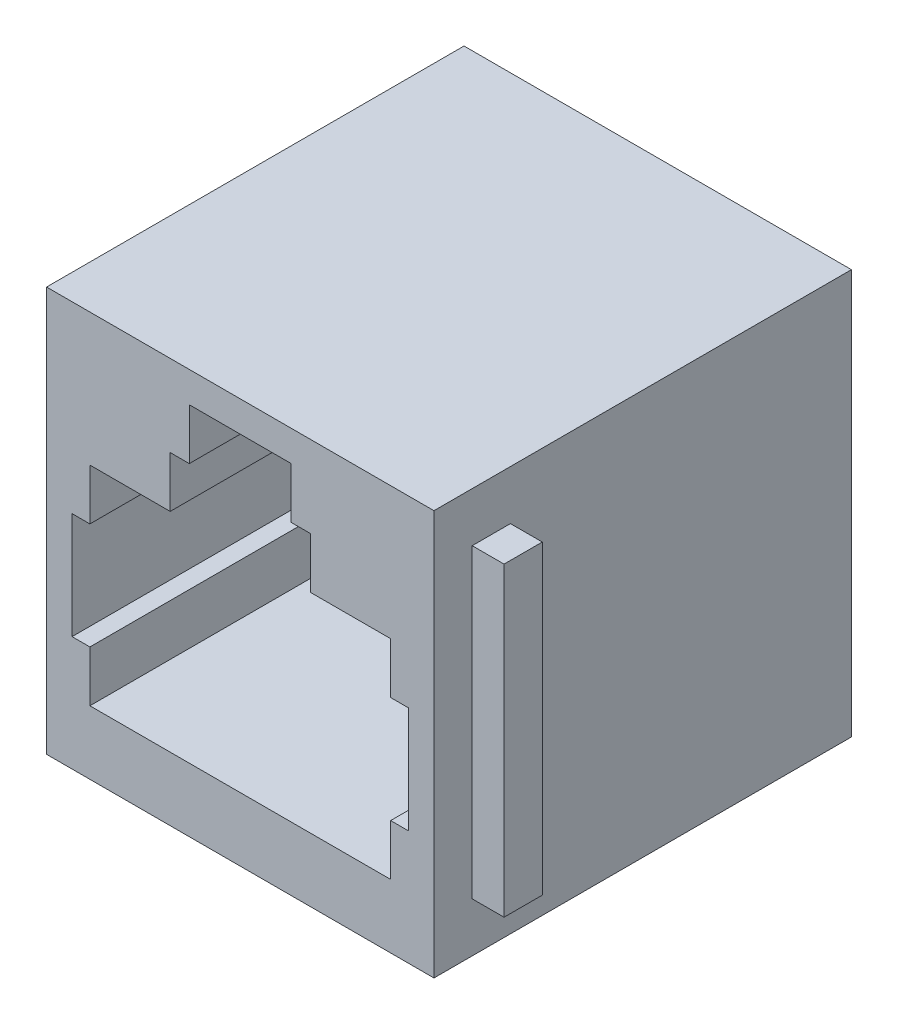
SolidWorks part; units mm, degrees
ref_plane "Front Plane" through (0, 0, 0) normal (0, 0, 1) x (1, 0, 0)
ref_plane "Top Plane" through (0, 0, 0) normal (0, 1, 0) x (1, 0, 0)
ref_plane "Right Plane" through (0, 0, 0) normal (1, 0, 0) x (0, 0, -1)
sketch "Sketch1" plane through (0, 0, 0) normal (0, 0, 1) x (1, 0, 0)
  line L0 (0, 0) -> (0, -7.94) construction
  line L1 (-7.6, 7.94) -> (7.6, 7.94)
  line L2 (-7.6, 7.94) -> (-7.6, -7.94)
  line L3 (-7.6, -7.94) -> (7.6, -7.94)
  line L4 (7.6, 7.94) -> (7.6, -7.94)
  line L5 (0, 0) -> (-7.6, 0) construction
  dimension "D1" = 15.88
  dimension "D2" = 15.2
extrude "Boss-Extrude1" add sketch "Sketch1" along normal blind 16.38
sketch "Sketch2" plane through (0, 0, 16.38) normal (0, 0, 1) x (1, 0, 0)
  line L0 (0, 0) -> (0, 6.74) construction
  line L1 (-2, 6.74) -> (2, 6.74)
  line L2 (2, 6.74) -> (2, 4.74)
  line L3 (2, 4.74) -> (2.75, 4.74)
  line L4 (2.75, 4.74) -> (2.75, 2.74)
  line L5 (2.75, 2.74) -> (5.9, 2.74)
  line L6 (5.9, 2.74) -> (5.9, 0.74)
  line L7 (5.9, 0.74) -> (6.6, 0.74)
  line L8 (6.6, 0.74) -> (6.6, -3.44)
  line L9 (6.6, -3.44) -> (5.9, -3.44)
  line L10 (5.9, -3.44) -> (5.9, -5.44)
  line L11 (5.9, -5.44) -> (-5.9, -5.44)
  line L12 (0, 0) -> (0, -5.44) construction
  line L13 (7.6, -7.94) -> (7.6, 7.94) construction
  line L14 (7.6, 7.94) -> (-7.6, 7.94) construction
  line L15 (-7.6, -7.94) -> (7.6, -7.94) construction
  line L16 (5.9, 0.74) -> (5.9, -3.44) construction
  line L17 (-5.9, -3.44) -> (-5.9, -5.44)
  line L18 (-6.6, -3.44) -> (-5.9, -3.44)
  line L19 (-5.9, 0.74) -> (-6.6, 0.74)
  line L20 (-6.6, 0.74) -> (-6.6, -3.44)
  line L21 (-5.9, 2.74) -> (-5.9, 0.74)
  line L22 (-2.75, 2.74) -> (-5.9, 2.74)
  line L23 (-2.75, 4.74) -> (-2.75, 2.74)
  line L24 (-2, 4.74) -> (-2.75, 4.74)
  line L25 (-2, 6.74) -> (-2, 4.74)
  point P8 (4.7, 1.6169)
  point P21 (4.7, 2.8427)
  point P22 (2.5785, 3.04)
  dimension "D1" = 1
  dimension "D2" = 1.2
  dimension "D3" = 2.5
  dimension "D4" = 2
  dimension "D5" = 0.7
  dimension "D6" = 2
  dimension "D7" = 4
  dimension "D8" = 5.5
extrude "Cut-Extrude1" cut sketch "Sketch2" against normal offset from surface (15.38 mm away) 1 up to face at (0, 0, 0)
sketch "Sketch3" plane through (0, 0, 0) normal (0, 1, 0) x (1, 0, 0)
  line L0 (0, 0) -> (0, -16.38) construction
  line L1 (7.6, -16.38) -> (-7.6, -16.38) construction
  line L2 (7.6, -16.38) -> (7.6, 0) construction
  line L3 (7.6, -13.38) -> (8.85, -13.38)
  line L4 (7.6, -13.38) -> (7.6, -14.88)
  line L5 (7.6, -14.88) -> (8.85, -14.88)
  line L6 (8.85, -13.38) -> (8.85, -14.88)
  line L7 (-8.85, -13.38) -> (-8.85, -14.88)
  line L8 (-7.6, -14.88) -> (-8.85, -14.88)
  line L9 (-7.6, -13.38) -> (-7.6, -14.88)
  line L10 (-7.6, -13.38) -> (-8.85, -13.38)
  dimension "D1" = 1.25
  dimension "D2" = 1.5
  dimension "D3" = 1.5
extrude "Boss-Extrude2" add sketch "Sketch3" along normal mid plane 12
